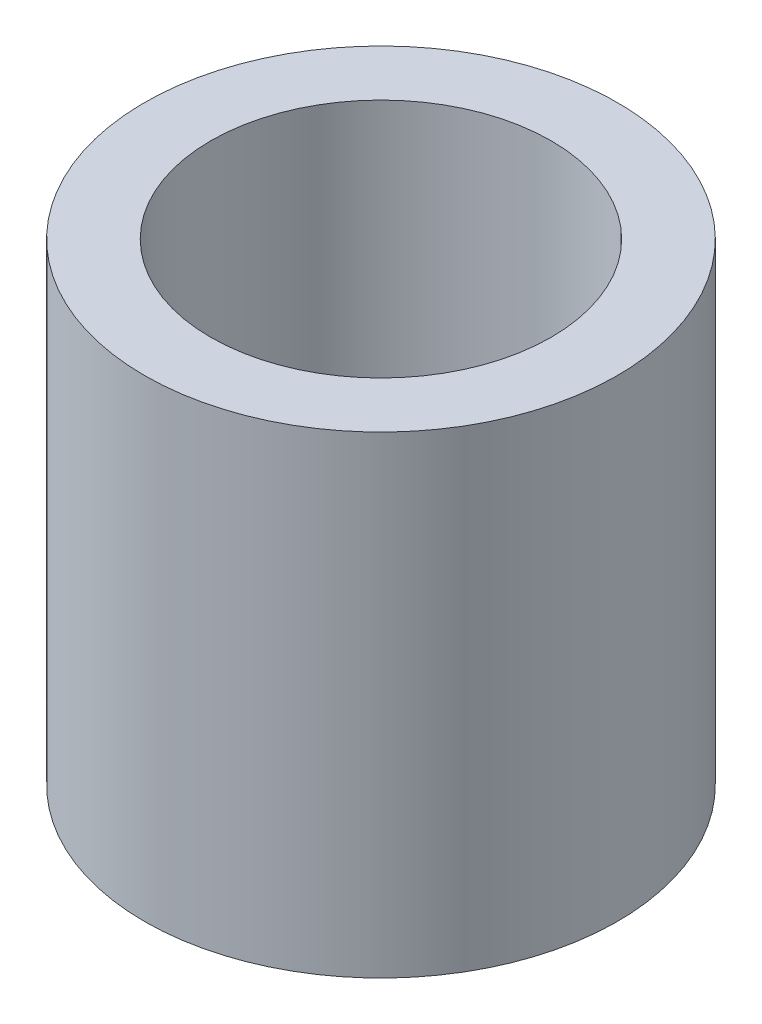
SolidWorks part; units mm, degrees
material "AISI 1020"
ref_plane "Front Plane" through (0, 0, 0) normal (0, 0, 1) x (1, 0, 0)
ref_plane "Top Plane" through (0, 0, 0) normal (0, 1, 0) x (1, 0, 0)
ref_plane "Right Plane" through (0, 0, 0) normal (1, 0, 0) x (0, 0, -1)
sketch "Sketch1" plane through (0, 0, 0) normal (0, 1, 0) x (1, 0, 0)
  circle A0 centre (0, 0) radius 12.5
  circle A1 centre (0, 0) radius 9
  dimension "D1" = 25
  dimension "D2" = 18
extrude "Boss-Extrude1" add sketch "Sketch1" along normal blind 25
